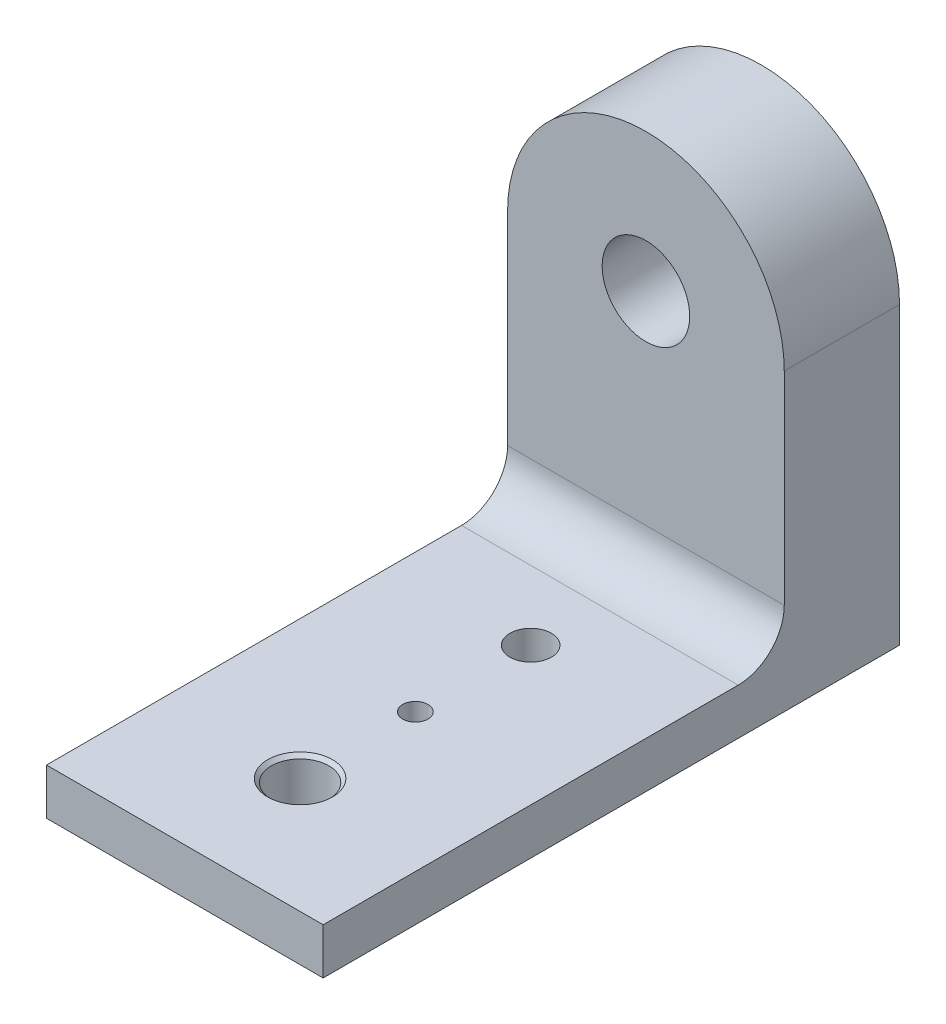
SolidWorks part; units mm, degrees
ref_plane "Front Plane" through (0, 0, 0) normal (0, 0, 1) x (1, 0, 0)
ref_plane "Top Plane" through (0, 0, 0) normal (0, 1, 0) x (1, 0, 0)
ref_plane "Right Plane" through (0, 0, 0) normal (1, 0, 0) x (0, 0, -1)
sketch "Sketch1" plane through (0, 0, 0) normal (0, 1, 0) x (1, 0, 0)
  line L1 (0, 0) -> (60, 0)
  line L2 (0, 0) -> (0, 125)
  line L3 (0, 125) -> (60, 125)
  line L4 (60, 0) -> (60, 125)
  dimension "D1" = 125
  dimension "D2" = 60
extrude "Boss-Extrude1" add sketch "Sketch1" along normal blind 10
sketch "Sketch2" plane through (0, 0, -125) normal (0, 0, -1) x (-1, 0, 0)
  line L0 (-60, 0) -> (0, 0) construction
  line L1 (-60, 10) -> (0, 10)
  line L2 (-60, 10) -> (-60, 64)
  line L3 (0, 10) -> (0, 0) construction
  line L4 (0, 10) -> (0, 64)
  arc A0 (0, 64) -> (-60, 64) centre (-30, 64) ccw
  circle A1 centre (-30, 64) radius 9.5
  dimension "D2" = 19
  dimension "D1" = 64
extrude "Boss-Extrude2" add sketch "Sketch2" against normal blind 25
sketch "Sketch3" plane through (0, 10, 0) normal (0, 1, 0) x (1, 0, 0)
  line L0 (60, 0) -> (60, 100) construction
  line L1 (0, 0) -> (60, 0) construction
  circle A0 centre (30, 50) radius 2.75
  dimension "D1" = 5.5
  dimension "D2" = 30
  dimension "D3" = 50
extrude "Cut-Extrude1" cut sketch "Sketch3" against normal up to next
sketch "Sketch4" plane through (0, 10, 0) normal (0, 1, 0) x (1, 0, 0)
  line L0 (30, 50) -> (30, 100) construction
  line L2 (0, 100) -> (60, 100) construction
  line L3 (30, 50) -> (30, 0) construction
  line L4 (0, 0) -> (60, 0) construction
  point P2 (0, 0)
  point P3 (0, 0)
  point P6 (30, 75)
  point P7 (30, 25)
  point P8 (30, 75)
  point P9 (0, 0)
hole_wizard "M10x1.0 Tapped Hole1" positions "Sketch5" profile "Sketch6" tap size "M10x1.0" standard "ANSI Metric" end condition through all
sketch "Sketch5" plane through (0, 10, 0) normal (0, 1, 0) x (1, 0, 0)
  point P0 (30, 75)
sketch "Sketch6" plane through (30, 10, -75) normal (1, 0, 0) x (0, 0, 1)
  line L0 (0, 0) -> (0, 10)
  line L1 (0, 10) -> (4.5, 10)
  line L2 (4.5, 10) -> (4.5, 0)
  line L5 (4.5, 0) -> (0, 0)
  line L11 (0, -6.35) -> (0, 107.95) construction
  dimension "Thru Tap Drill Dia." = 9
  dimension "Thru Tap Drill Depth" = 10
cosmetic thread "Hole Thread1" parameters "D2"=10
hole_wizard "M14x1.5 Tapped Hole1" positions "Sketch9" profile "Sketch10" tap size "M14x1.5" standard "ANSI Metric" end condition through all
sketch "Sketch9" plane through (0, 10, 0) normal (0, 1, 0) x (1, 0, 0)
  point P0 (30, 25)
sketch "Sketch10" plane through (30, 10, -25) normal (1, 0, 0) x (0, 0, 1)
  line L0 (0, 0) -> (0, 10)
  line L1 (0, 10) -> (6.25, 10)
  line L2 (6.25, 10) -> (6.25, 0.775)
  line L3 (6.25, 0.775) -> (7.025, 0)
  line L5 (7.025, 0) -> (0, 0)
  line L6 (-6.25, 0.775) -> (-7.025, 0) construction
  line L11 (0, -6.35) -> (0, 107.95) construction
  dimension "Thru Tap Drill Dia." = 12.5
  dimension "Thru Tap Drill Depth" = 10
  dimension "Near C'Sink Dia." = 14.05
  dimension "Near C'Sink Angle" = 90
cosmetic thread "Hole Thread2" parameters "D2"=14
fillet "Fillet1" radius 10 1 edges
